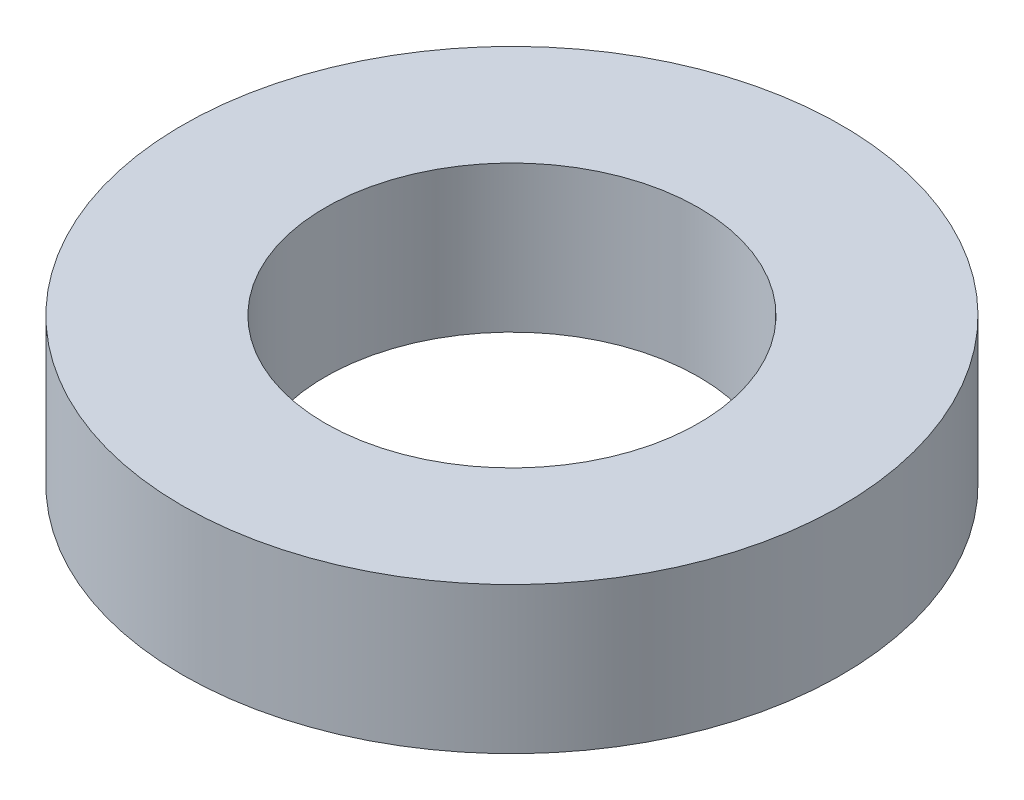
SolidWorks part; units mm, degrees
ref_plane "Front Plane" through (0, 0, 0) normal (0, 0, 1) x (1, 0, 0)
ref_plane "Top Plane" through (0, 0, 0) normal (0, 1, 0) x (1, 0, 0)
ref_plane "Right Plane" through (0, 0, 0) normal (1, 0, 0) x (0, 0, -1)
sketch "Sketch3" plane through (0, 0, 0) normal (0, 1, 0) x (1, 0, 0)
  circle A0 centre (0, 0) radius 4.5
  circle A1 centre (0, 0) radius 2.55
  dimension "D1" = 9
  dimension "D2" = 5.1
extrude "Boss-Extrude1" add sketch "Sketch3" along normal blind 2
equation "\"D_OUT\"=9"
equation "\"D1@Sketch3\"=\"D_OUT\""
equation "\"D_IN\"= 5 + \"IN_TOL\""
equation "\"D2@Sketch3\"=\"D_IN\""
equation "\"THICK\"= 2"
equation "\"D1@Boss-Extrude1\"=\"THICK\""
equation "\"IN_TOL\"= 0.1"
